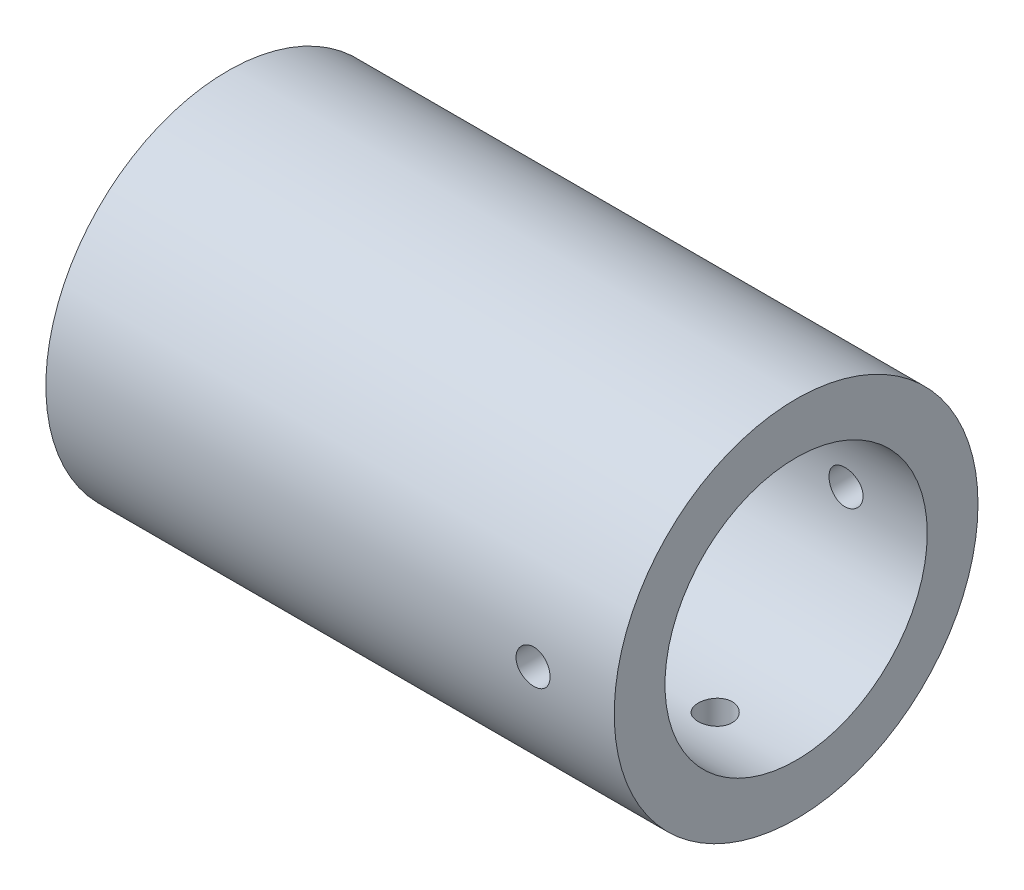
SolidWorks part; units mm, degrees
material "1060 Alloy"
ref_plane "Front Plane" through (0, 0, 0) normal (0, 0, 1) x (1, 0, 0)
ref_plane "Top Plane" through (0, 0, 0) normal (0, 1, 0) x (1, 0, 0)
ref_plane "Right Plane" through (0, 0, 0) normal (1, 0, 0) x (0, 0, -1)
sketch "Sketch1" plane through (0, 0, 0) normal (1, 0, 0) x (0, 0, -1)
  circle A0 centre (0, 0) radius 22.4
  dimension "D1" = 44.8
extrude "Extrude1" add sketch "Sketch1" along normal blind 70
sketch "Sketch2" plane through (70, 0, 0) normal (1, 0, 0) x (0, 0, -1)
  circle A0 centre (0, 0) radius 16.15
  dimension "D1" = 32.3
extrude "Extrude2" cut sketch "Sketch2" against normal blind 64
sketch "Sketch3" plane through (0, 0, 0) normal (-1, 0, 0) x (0, 0, 1)
  circle A0 centre (0, 0) radius 5
  dimension "D1" = 10
extrude "Extrude3" cut sketch "Sketch3" against normal blind 10
sketch "Sketch7" plane through (0, 0, 0) normal (0, 1, 0) x (1, 0, 0)
  line L0 (-24.64, 0) -> (24.64, 0) construction
  line L1 (9, 12.5) -> (43, 12.5)
  line L2 (6, 9.5) -> (6, -9.5)
  line L3 (9, -12.5) -> (43, -12.5)
  line L4 (46, 9.5) -> (46, -9.5)
  line L5 (6, 12.5) -> (46, -12.5) construction
  line L6 (6, -12.5) -> (46, 12.5) construction
  line L7 (0, -24.64) -> (0, 24.64) construction
  arc A0 (9, -12.5) -> (6, -9.5) centre (9, -9.5) cw
  arc A1 (43, -12.5) -> (46, -9.5) centre (43, -9.5) ccw
  arc A2 (43, 12.5) -> (46, 9.5) centre (43, 9.5) cw
  arc A3 (6, 9.5) -> (9, 12.5) centre (9, 9.5) cw
  point P0 (26, 0)
  dimension "D4" = 3
  dimension "D1" = 40
  dimension "D2" = 25
  dimension "D3" = 6
extrude "Extrude5" cut sketch "Sketch7" against normal blind 30
hole_wizard "M5 Tapped Hole3" positions "3DSketch1" profile "Sketch8" tap size "M5" standard "ISO" end condition through all
sketch3d "3DSketch1"
  point P14 (60, 0, 22.4)
sketch "Sketch8" plane through (60, 0, 22.4) normal (1, 0, 0) x (0, -1, 0)
  line L0 (0, 0) -> (0, 44.8)
  line L1 (0, 44.8) -> (2.1, 44.8)
  line L2 (2.1, 44.8) -> (2.1, 0)
  line L5 (2.1, 0) -> (0, 0)
  line L11 (0, -6.35) -> (0, 107.95) construction
  dimension "Thru Tap Drill Dia." = 4.2
  dimension "Thru Tap Drill Depth" = 44.8
cosmetic thread "Hole Thread1" parameters "D2"=5
hole_wizard "M5 Tapped Hole5" positions "3DSketch4" profile "Sketch11" tap size "M5" standard "ISO"
sketch3d "3DSketch4"
  circle A0 centre (70, 0, 0) radius 22.4 construction
  point P0 (59.9474, -16.1498, -0.0837)
  point P5 (92.4, 0, 0)
  dimension "D1" = 19.0231
sketch "Sketch11" plane through (59.9474, -16.1498, -0.0837) normal (1, 0, 0) x (0, -0.0052, 1)
  line L0 (0, 0) -> (0, 15.2618)
  line L1 (0, 15.2618) -> (2.1, 14)
  line L2 (2.1, 14) -> (2.1, 0)
  line L5 (2.1, 0) -> (0, 0)
  line L10 (0, 15.2618) -> (-2.1, 14) construction
  line L11 (0, -6.35) -> (0, 107.95) construction
  dimension "Tap Drill Dia." = 4.2
  dimension "Tap Drill Depth" = 14
  dimension "Drill Angle" = 118
cosmetic thread "Hole Thread4" parameters "D1"=6.3871, "D2"=5
sketch "Sketch12" plane through (0, 0, 0) normal (-1, 0, 0) x (0, 0, 1)
  line L0 (0, 0) -> (0, 23.1093)
  line L1 (0, 23.1093) -> (0, -22.4)
  line L2 (-22.4, 0) -> (22.4, 0)
  circle A0 centre (0, 0) radius 15
  circle A1 centre (0, 0) radius 22.4 construction
  dimension "D1" = 30
hole_wizard "M4 Tapped Hole1" positions "3DSketch5" profile "Sketch13" tap size "M4" standard "ISO"
sketch3d "3DSketch5"
  line L0 (0, 0, -22.4) -> (0, 0, 22.4) construction
  line L1 (0, 0, 0) -> (0, 23.1093, 0) construction
  line L2 (0, 23.1093, 0) -> (0, -22.4, 0) construction
  circle A0 centre (0, 0, 0) radius 15 construction
  point P0 (0, 0, -15.0274)
  point P4 (0, 15, 0)
  point P10 (-15, 0, 0)
  point P11 (0, 0, 15)
  point P13 (0, -15, 0)
sketch "Sketch13" plane through (0, 0, -15.0274) normal (0, 1, 0) x (0, 0, 1)
  line L0 (0, 0) -> (0, 12.4914)
  line L1 (0, 12.4914) -> (1.65, 11.5)
  line L2 (1.65, 11.5) -> (1.65, 0)
  line L5 (1.65, 0) -> (0, 0)
  line L10 (0, 12.4914) -> (-1.65, 11.5) construction
  line L11 (0, -6.35) -> (0, 107.95) construction
  dimension "Tap Drill Dia." = 3.3
  dimension "Tap Drill Depth" = 11.5
  dimension "Drill Angle" = 118
cosmetic thread "Hole Thread5" parameters "D1"=6, "D2"=4
cosmetic thread "Hole Thread6" parameters "D1"=8, "D2"=4
cosmetic thread "Hole Thread7" parameters "D1"=8, "D2"=4
cosmetic thread "Hole Thread8" parameters "D1"=8, "D2"=4
